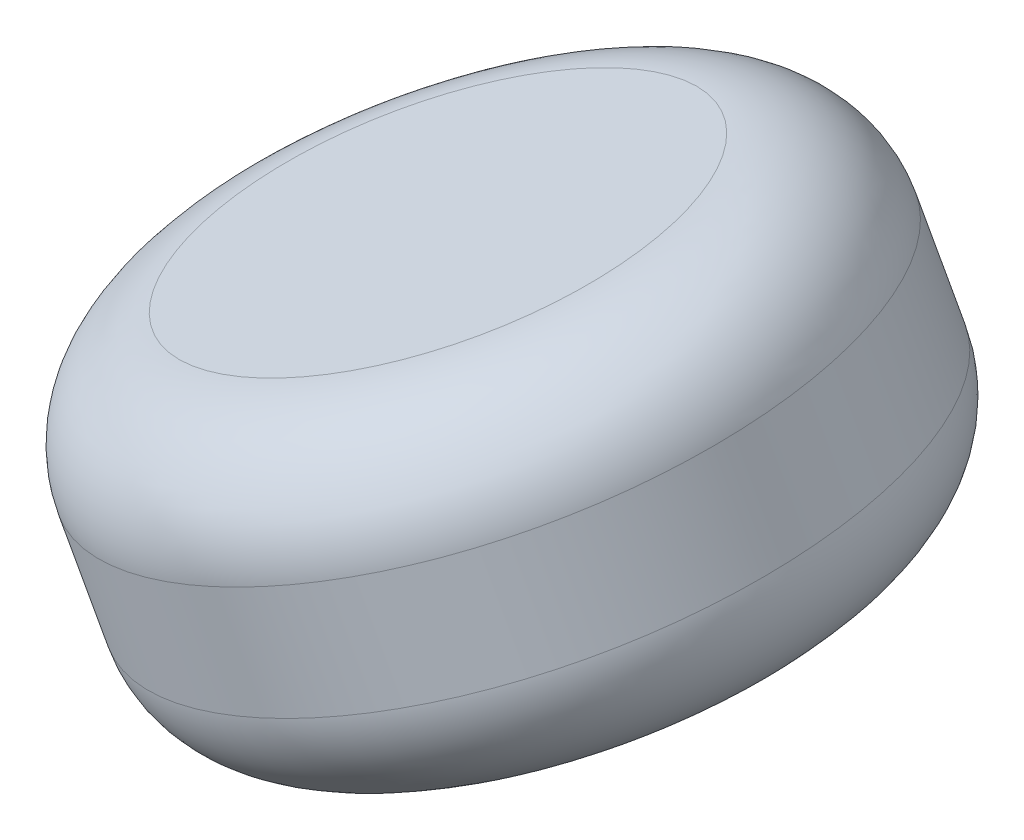
SolidWorks part; units mm, degrees
material "Neodymium Magnet (NdFeB)"
ref_plane "Front Plane" through (0, 0, 0) normal (0, 0, 1) x (1, 0, 0)
ref_plane "Top Plane" through (0, 0, 0) normal (0, 1, 0) x (1, 0, 0)
ref_plane "Right Plane" through (0, 0, 0) normal (1, 0, 0) x (0, 0, -1)
sketch "Sketch1" plane through (-109.9166, 289.2625, 32.3522) normal (0.3533, -0.9297, -0.104) x (-0.72, -0.1993, -0.6647)
  circle A0 centre (0, 0) radius 3
  dimension "D1" = 6
extrude "Boss-Extrude1" add sketch "Sketch1" against normal blind 3
fillet "Fillet2" radius 1 2 edges at (-108.1721, 293.1172, 32.6641) (-107.1122, 290.3281, 32.3522)
equation "\"D1@Sketch1\"=\"MAG_MagnetDia\""
equation "\"D1@Boss-Extrude1\"=\"MAG_MagnetThk\""
equation "\"____ GENERATED PART EXPORTS ____\" = 0"
equation "\"SYS_VersionTag\" = 2"
equation "\"MAG_MagnetDia\" = 6mm"
equation "\"MAG_MagnetThk\" = 3mm"
